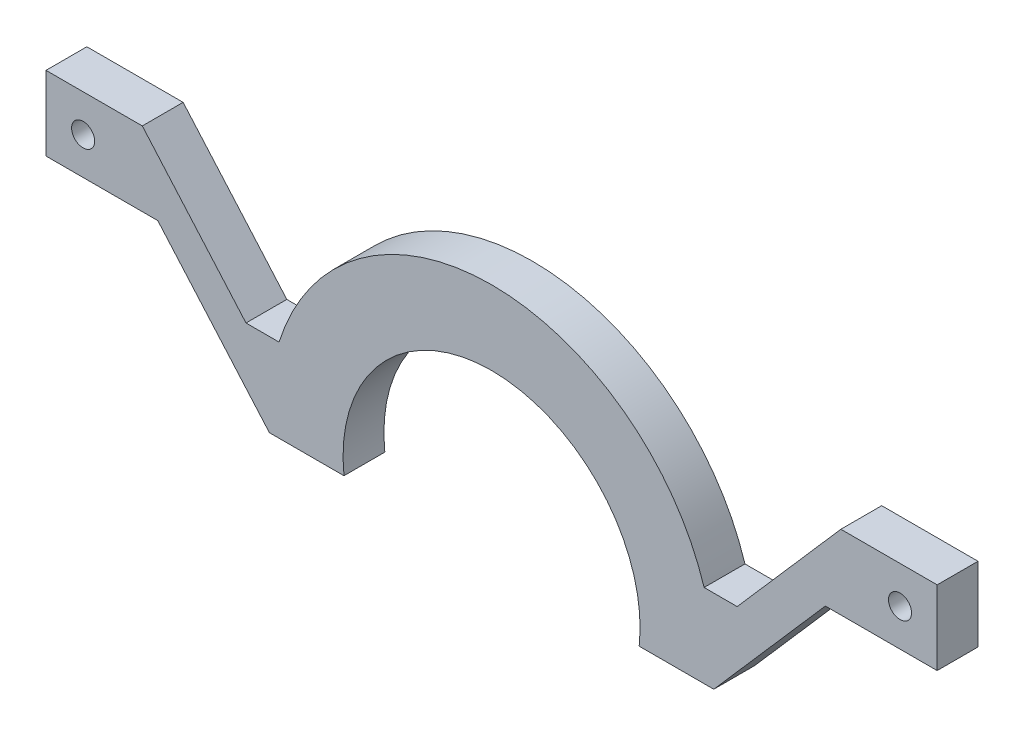
SolidWorks part; units mm, degrees
material "ﾁｰｸ材"
ref_plane "正面" through (0, 0, 0) normal (0, 0, 1) x (1, 0, 0)
ref_plane "平面" through (0, 0, 0) normal (0, 1, 0) x (1, 0, 0)
ref_plane "右側面" through (0, 0, 0) normal (1, 0, 0) x (0, 0, -1)
sketch "ｽｹｯﾁ1" plane through (0, 0, 0) normal (0, 0, 1) x (1, 0, 0)
  line L0 (-60, 5) -> (-47.0333, 5)
  line L2 (60, 5) -> (60, -5)
  line L4 (-60, 5) -> (-60, -5)
  line L5 (60, 5) -> (-60, -5) construction
  line L6 (60, -5) -> (-60, 5) construction
  line L7 (-60, -5) -> (-44.943, -5)
  line L8 (29.5804, -15) -> (47.0333, 5) construction
  line L9 (-29.5804, -15) -> (-47.0333, 5) construction
  line L10 (-44.943, -5) -> (-29.9179, -22.2178)
  line L11 (-47.0333, 5) -> (-33.071, -11)
  line L12 (-29.9179, -22.2178) -> (-19.8767, -22.2178)
  line L13 (-33.071, -11) -> (-28.6182, -11)
  line L14 (28.6182, -11) -> (33.071, -11)
  line L15 (33.071, -11) -> (47.0333, 5)
  line L16 (60, -5) -> (44.943, -5)
  line L17 (19.8767, -22.2178) -> (29.9179, -22.2178)
  line L18 (29.9179, -22.2178) -> (44.943, -5)
  line L19 (47.0333, 5) -> (60, 5)
  circle A0 centre (0, -20) radius 30 construction
  arc A1 (19.8767, -22.2178) -> (-19.8767, -22.2178) centre (0, -20) ccw
  arc A2 (-28.6182, -11) -> (28.6182, -11) centre (0, -20) cw
  point P0 (0, 0)
  dimension "D3" = 60
  dimension "D10" = 40
  dimension "D11" = 9
  dimension "D1" = 10
  dimension "D2" = 120
  dimension "D4" = 25
  dimension "D5" = 5
  dimension "D6" = 5
  dimension "D7" = 19
  dimension "D8" = 19
  dimension "D9" = 5
extrude "ﾎﾞｽ - 押し出し1" add sketch "ｽｹｯﾁ1" along normal blind 5.5
sketch "ｽｹｯﾁ2" plane through (0, 0, 5.5) normal (0, 0, 1) x (1, 0, 0)
  line L0 (-60, 5) -> (-60, -5) construction
  line L1 (60, -5) -> (60, 5) construction
  circle A0 centre (-55, 0) radius 1.55
  circle A1 centre (55, 0) radius 1.55
  dimension "D1" = 3.1
  dimension "D2" = 5
  dimension "D3" = 5
extrude "ｶｯﾄ - 押し出し1" cut sketch "ｽｹｯﾁ2" against normal through all
